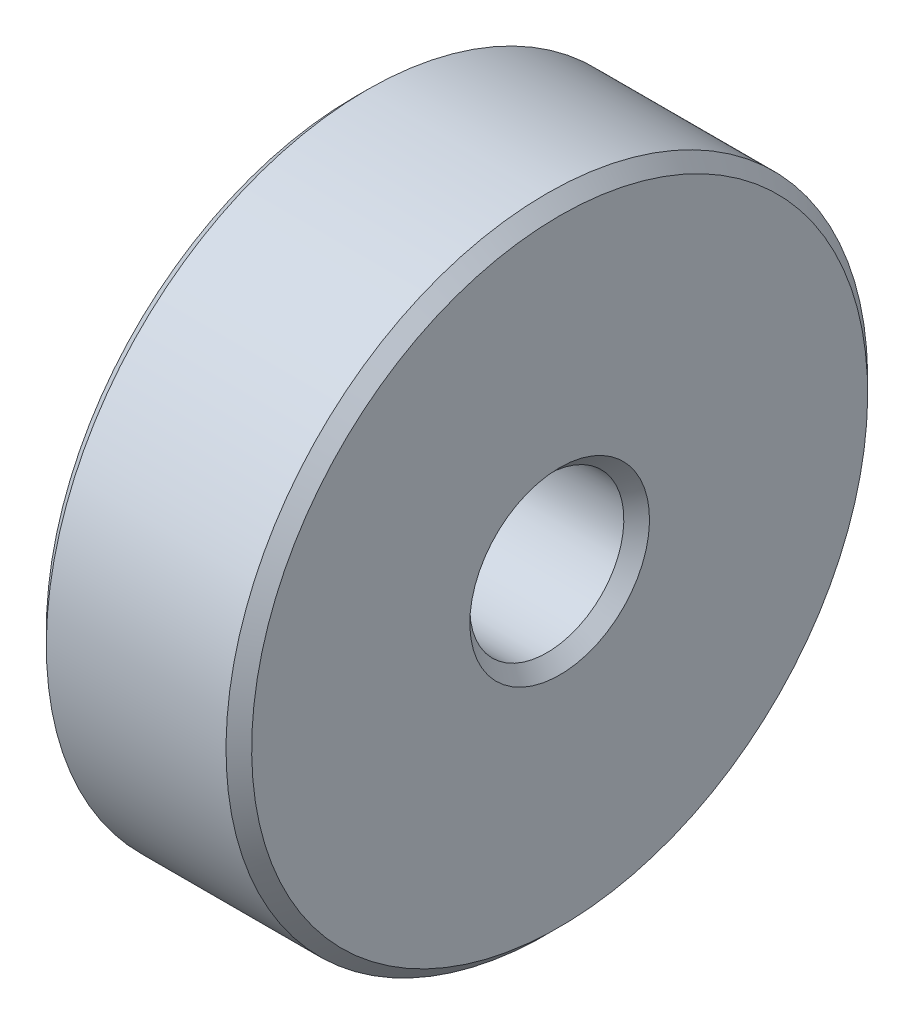
SolidWorks part; units mm, degrees
ref_plane "正面" through (0, 0, 0) normal (0, 0, 1) x (1, 0, 0)
ref_plane "平面" through (0, 0, 0) normal (0, 1, 0) x (1, 0, 0)
ref_plane "右側面" through (0, 0, 0) normal (1, 0, 0) x (0, 0, -1)
ref_plane "平面1" through (0, 0, 0) normal (0, 0, 1) x (1, 0, 0)
sketch "ｽｹｯﾁ1" plane through (0, 0, 0) normal (0, 0, 1) x (1, 0, 0)
  line L0 (0, -3.5) -> (0, -12)
  line L1 (0, -12) -> (0.5, -12.5)
  line L2 (0.5, -12.5) -> (7.5, -12.5)
  line L3 (7.5, -12.5) -> (8, -12)
  line L4 (8, -12) -> (8, -3.5)
  line L5 (8, -3.5) -> (7.5, -3)
  line L6 (7.5, -3) -> (0.5, -3)
  line L7 (0.5, -3) -> (0, -3.5)
  line L8 (-3, 0) -> (3, 0) construction
revolve "回転1" add sketch "ｽｹｯﾁ1" angle 360 about L8
